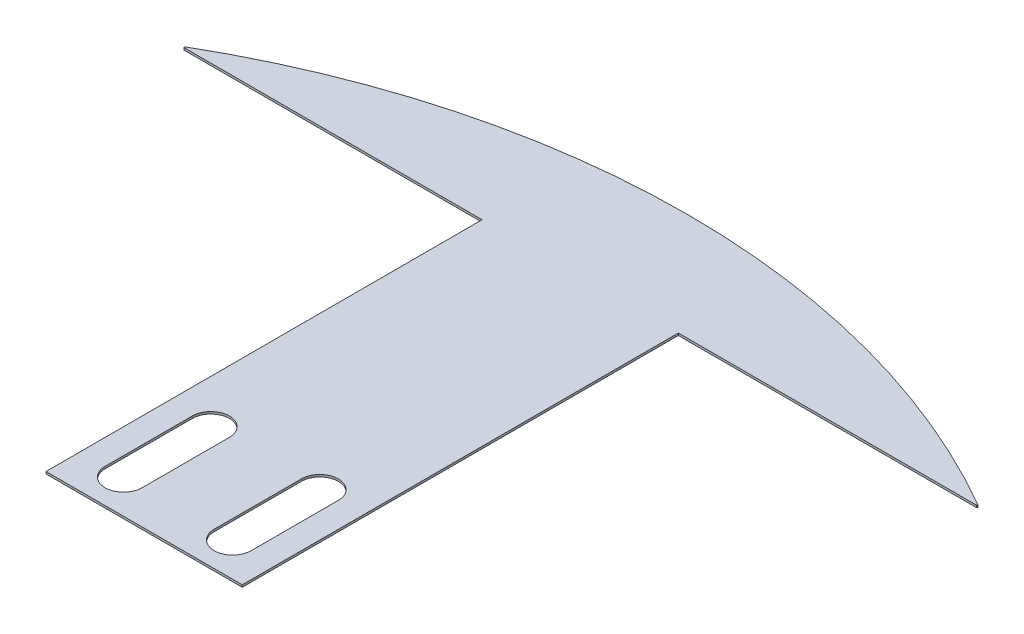
SolidWorks part; units mm, degrees
material "Galvanized Steel"
ref_plane "Front Plane" through (0, 0, 0) normal (0, 0, 1) x (1, 0, 0)
ref_plane "Top Plane" through (0, 0, 0) normal (0, 1, 0) x (1, 0, 0)
ref_plane "Right Plane" through (0, 0, 0) normal (1, 0, 0) x (0, 0, -1)
sketch "Sketch1" plane through (0, 0, 0) normal (0, 1, 0) x (1, 0, 0)
  line L0 (-1000, 0) -> (49000, 0) construction
  line L1 (0, -1000) -> (0, 49000) construction
  line L2 (-500, -866.0254) -> (24500, 42435.2448) construction
  line L3 (-500, 866.0254) -> (24500, -42435.2448) construction
  line L10 (-22.5, 57.3948) -> (22.5, 57.3948)
  line L11 (-22.5, 57.3948) -> (-22.5, 157.3948)
  line L13 (22.5, 57.3948) -> (22.5, 157.3948)
  line L14 (-22.5, 57.3948) -> (3.1123, 176.2089) construction
  line L15 (-10.9254, 212.4537) -> (22.5, 57.3948) construction
  line L17 (-16.75, 85.1948) -> (-16.75, 65.1948)
  line L19 (-8.25, 85.1948) -> (-8.25, 65.1948)
  line L21 (16.75, 85.1948) -> (16.75, 65.1948)
  line L22 (8.25, 85.1948) -> (8.25, 65.1948)
  line L24 (-90.8719, 157.3948) -> (-22.5, 157.3948)
  line L27 (-12.5, 65.1948) -> (-12.5, 85.1948) construction
  line L29 (12.5, 85.1948) -> (12.5, 65.1948) construction
  line L30 (22.5, 157.3948) -> (90.8719, 157.3948)
  line L32 (91, 157.6166) -> (90.8719, 157.3948)
  line L34 (-90.8719, 157.3948) -> (-91, 157.6166)
  circle A0 centre (0, 0) radius 400 construction
  arc A27 (-16.75, 85.1948) -> (-8.25, 85.1948) centre (-12.5, 85.1948) cw
  arc A28 (-8.25, 65.1948) -> (-16.75, 65.1948) centre (-12.5, 65.1948) cw
  arc A29 (16.75, 85.1948) -> (8.25, 85.1948) centre (12.5, 85.1948) ccw
  arc A30 (8.25, 65.1948) -> (16.75, 65.1948) centre (12.5, 65.1948) ccw
  arc A31 (-91, 157.6166) -> (91, 157.6166) centre (0, 0) cw
  arc A32 (-91, -157.6166) -> (182, 0) centre (0, 0) ccw construction
  arc A33 (91, 157.6166) -> (-91, 157.6166) centre (0, 0) ccw construction
  point P12 (0, 161.7712)
  point P14 (0, 209)
  point P15 (0, 215)
  dimension "D1" = 800
  dimension "D4" = 182
  dimension "D5" = 6
  dimension "D8" = 4.25
  dimension "D9" = 100
  dimension "D12" = 4.25
  dimension "D13" = 4.25
  dimension "D6" = 45
  dimension "D7" = 25
  dimension "D10" = 7.8
  dimension "D2" = 60
  dimension "D3" = 60
  dimension "D11" = 20
extrude "Boss-Extrude1" add sketch "Sketch1" along normal mid plane 0.5
